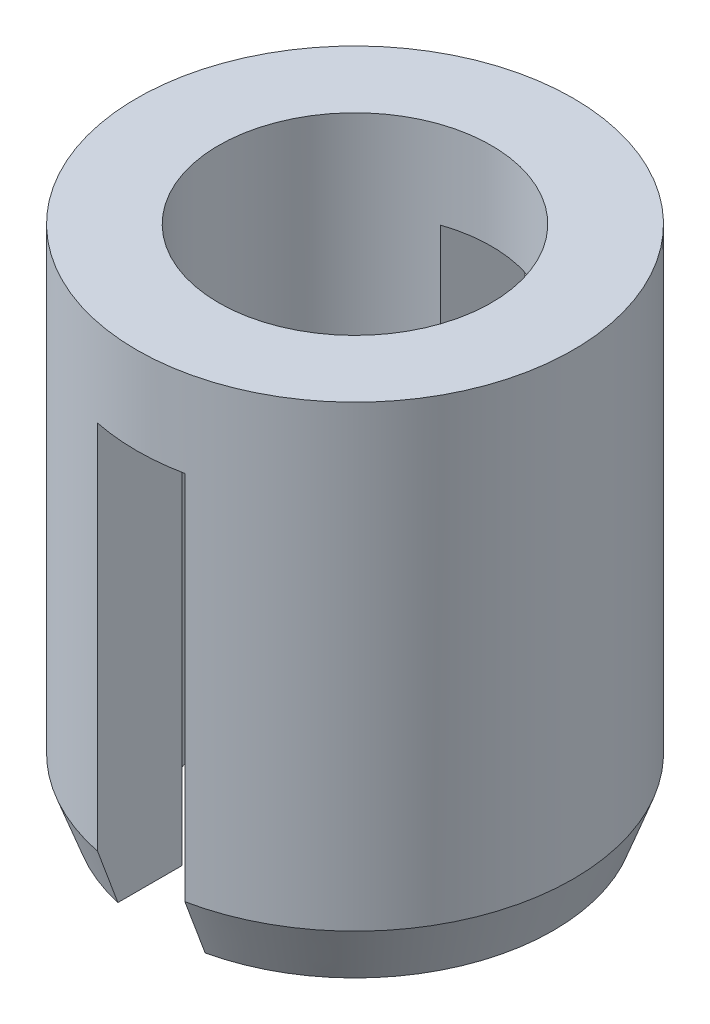
SolidWorks part; units mm, degrees
ref_plane "Front Plane" through (0, 0, 0) normal (0, 0, 1) x (1, 0, 0)
ref_plane "Top Plane" through (0, 0, 0) normal (0, 1, 0) x (1, 0, 0)
ref_plane "Right Plane" through (0, 0, 0) normal (1, 0, 0) x (0, 0, -1)
sketch "Sketch1" plane through (0, 0, 0) normal (0, 0, 1) x (1, 0, 0)
  line L0 (0, -4.7) -> (0, 0)
  line L1 (0, 0) -> (-2, 0)
  line L2 (-2, 0) -> (-2, -4.2)
  line L3 (-2, -4.2) -> (-1.818, -4.7)
  line L4 (-1.818, -4.7) -> (0, -4.7)
  line L5 (0, -4.7) -> (0, -6.7522) construction
  dimension "D1" = 4.7
  dimension "D2" = 4
  dimension "D3" = 0.5
  dimension "D4" = 20
revolve "Revolve1" add sketch "Sketch1" angle 360 about L5
hole_wizard "M3 Tapped Hole1" positions "Sketch3" profile "Sketch5" tap size "M3" standard "ISO" end condition through all
sketch "Sketch3" plane through (0, 0, 0) normal (0, 1, 0) x (1, 0, 0)
  point P0 (0, 0)
sketch "Sketch5" plane through (0, 0, 0) normal (1, 0, 0) x (0, 0, 1)
  line L0 (0, 0) -> (0, 4.7)
  line L1 (0, 4.7) -> (1.25, 4.7)
  line L2 (1.25, 4.7) -> (1.25, 0)
  line L5 (1.25, 0) -> (0, 0)
  line L11 (0, -6.35) -> (0, 107.95) construction
  dimension "Thru Tap Drill Dia." = 2.5
  dimension "Thru Tap Drill Depth" = 4.7
cosmetic thread "Hole Thread1" parameters "D2"=3
sketch "Sketch2" plane through (0, 0, 0) normal (0, 0, 1) x (1, 0, 0)
  line L0 (-1.25, -4.7) -> (1.25, -4.7) construction
  line L1 (0.4, -0.8) -> (-0.4, -0.8)
  line L2 (0.4, -0.8) -> (0.4, -4.7)
  line L3 (0.4, -4.7) -> (-0.4, -4.7)
  line L4 (-0.4, -0.8) -> (-0.4, -4.7)
  point P4 (0, -0.8)
  dimension "D1" = 0.8
  dimension "D2" = 0.8
extrude "Cut-Extrude1" cut sketch "Sketch2" against normal through all both and the other way through all
other "Freeze***"
